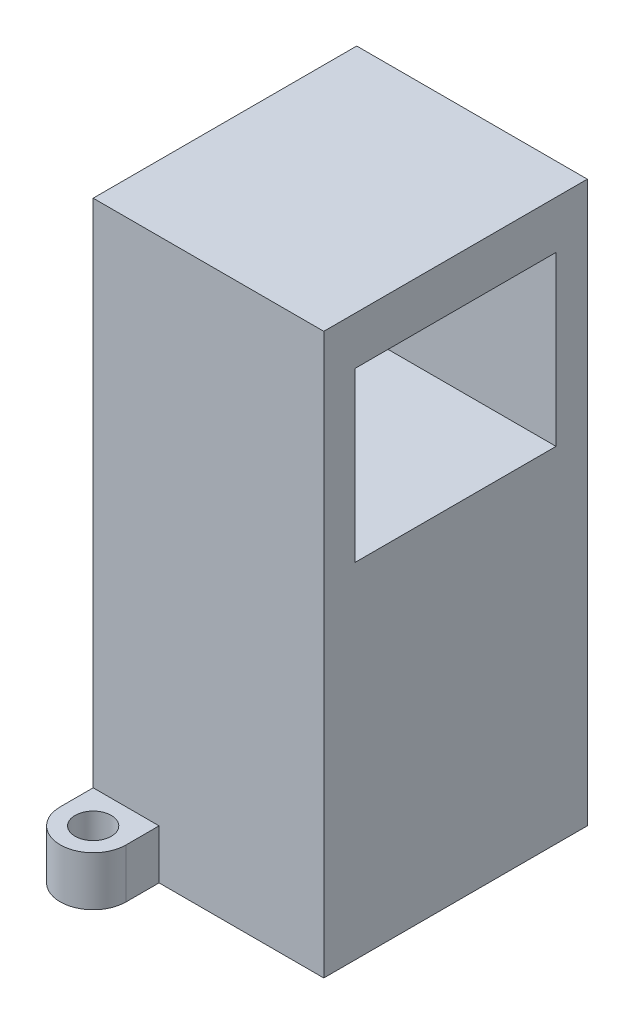
SolidWorks part; units mm, degrees
ref_plane "前视基准面" through (0, 0, 0) normal (0, 0, 1) x (1, 0, 0)
ref_plane "上视基准面" through (0, 0, 0) normal (0, 1, 0) x (1, 0, 0)
ref_plane "右视基准面" through (0, 0, 0) normal (1, 0, 0) x (0, 0, -1)
sketch "草图1" plane through (0, 0, 0) normal (0, 1, 0) x (1, 0, 0)
  line L0 (-31.6345, 0) -> (31.6345, 0) construction
  line L1 (0, 31.5533) -> (0, -31.5533) construction
  line L3 (-7, 8) -> (7, 8)
  line L4 (-7, 8) -> (-7, -8)
  line L5 (-7, -8) -> (7, -8)
  line L6 (7, 8) -> (7, -8)
  line L7 (-7, 8) -> (7, -8) construction
  line L8 (-7, -8) -> (7, 8) construction
  point P0 (0, 0)
  point P4 (0, 0)
  point P8 (0, 0)
  dimension "D1" = 16
  dimension "D2" = 14
extrude "凸台-拉伸1" add sketch "草图1" along normal blind 34
sketch "草图2" plane through (0, 0, 0) normal (1, 0, 0) x (0, 0, -1)
  line L0 (0, 0) -> (0, 36.7791) construction
  line L1 (-13.0606, 26) -> (13.0606, 26) construction
  line L2 (-8, 0) -> (8, 0) construction
  line L4 (-6.1, 31.1) -> (6.1, 31.1)
  line L5 (-6.1, 31.1) -> (-6.1, 20.9)
  line L6 (-6.1, 20.9) -> (6.1, 20.9)
  line L7 (6.1, 31.1) -> (6.1, 20.9)
  line L8 (-6.1, 31.1) -> (6.1, 20.9) construction
  line L9 (-6.1, 20.9) -> (6.1, 31.1) construction
  circle A1 centre (0, 26) radius 3.2856 construction
  point P6 (0, 26)
  point P8 (0, 26)
  dimension "D1" = 26
  dimension "D2" = 10.2
  dimension "D3" = 12.2
extrude "切除-拉伸1" cut sketch "草图2" against normal through all both and the other way through all
sketch "草图3" plane through (0, 0, 0) normal (0, 1, 0) x (1, 0, 0)
  line L0 (-7, 8) -> (-7, 10)
  line L2 (7, 8) -> (-7, 8) construction
  line L6 (-3, 10) -> (-3, 8)
  line L7 (-3, 8) -> (-7, 8)
  circle A2 centre (-5, 10) radius 1.1
  arc A3 (-3, 10) -> (-7, 10) centre (-5, 10) ccw
  point P4 (0, 0)
  dimension "D2" = 2
  dimension "D3" = 2.2
  dimension "D1" = 4
extrude "凸台-拉伸2" add sketch "草图3" along normal blind 3
mirror "镜向1" about plane through (0, 0, 0) normal (0, 0, 1) of "凸台-拉伸2"
